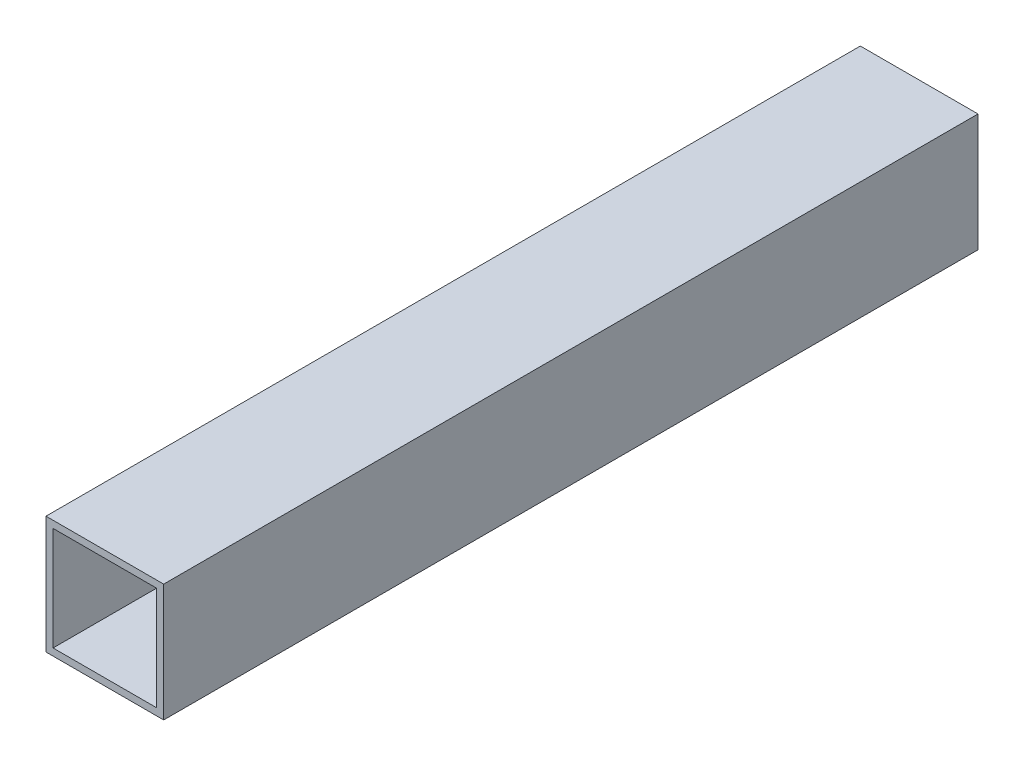
SolidWorks part; units mm, degrees
ref_plane "Ebene vorne" through (0, 0, 0) normal (0, 0, 1) x (1, 0, 0)
ref_plane "Ebene oben" through (0, 0, 0) normal (0, 1, 0) x (1, 0, 0)
ref_plane "Ebene rechts" through (0, 0, 0) normal (1, 0, 0) x (0, 0, -1)
sketch "Skizze1" plane through (0, 0, 0) normal (0, 0, 1) x (1, 0, 0)
  line L1 (-12.5, -12.5) -> (12.5, -12.5)
  line L2 (-12.5, -12.5) -> (-12.5, 12.5)
  line L3 (-12.5, 12.5) -> (12.5, 12.5)
  line L4 (12.5, -12.5) -> (12.5, 12.5)
  line L5 (-12.5, -12.5) -> (12.5, 12.5) construction
  line L6 (-12.5, 12.5) -> (12.5, -12.5) construction
  point P0 (0, 0)
  dimension "D1" = 25
  dimension "D2" = 25
extrude "Linear-Austragen-Dünn1" add sketch "Skizze1" along normal blind 173 thin thin type one direction reverse wall 1.5
